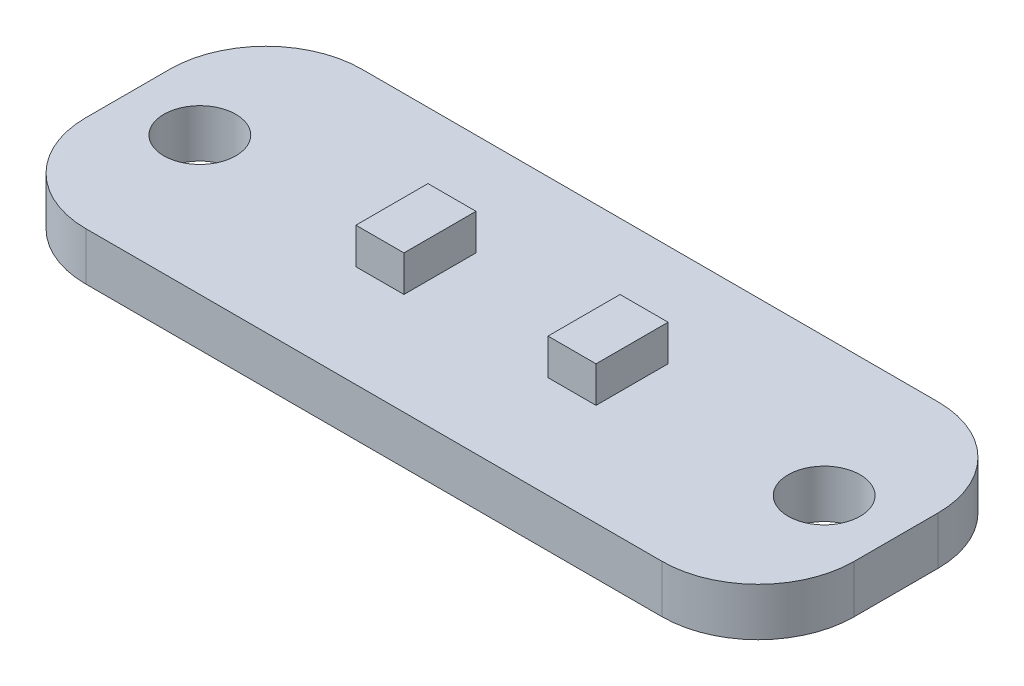
SolidWorks part; units mm, degrees
ref_plane "Front Plane" through (0, 0, 0) normal (0, 0, 1) x (1, 0, 0)
ref_plane "Top Plane" through (0, 0, 0) normal (0, 1, 0) x (1, 0, 0)
ref_plane "Right Plane" through (0, 0, 0) normal (1, 0, 0) x (0, 0, -1)
sketch "Sketch1" plane through (0, 0, 0) normal (0, 1, 0) x (1, 0, 0)
  line L1 (0, 0) -> (32, 0)
  line L2 (0, 0) -> (0, -11.5)
  line L3 (0, -11.5) -> (32, -11.5)
  line L4 (32, 0) -> (32, -11.5)
  dimension "D1" = 32
  dimension "D2" = 11.5
extrude "Boss-Extrude1" add sketch "Sketch1" along normal blind 2
sketch "Sketch2" plane through (0, 2, 0) normal (0, 1, 0) x (1, 0, 0)
  line L0 (32, -11.5) -> (32, 0) construction
  line L1 (0, 0) -> (0, -11.5) construction
  circle A0 centre (3, -5.75) radius 1.5
  circle A1 centre (29, -5.75) radius 1.5
  point P4 (0, 0)
  point P7 (32, -5.75)
  point P10 (0, -5.75)
  dimension "D1" = 3
  dimension "D2" = 3
  dimension "D3" = 3
  dimension "D4" = 3
extrude "Cut-Extrude1" cut sketch "Sketch2" against normal through all
fillet "Fillet1" radius 4 4 edges at (32, 1, 0) (32, 1, 11.5) (0, 1, 0) (0, 1, 11.5)
sketch "Sketch3" plane through (0, 2, 0) normal (0, 1, 0) x (1, 0, 0)
  line L0 (32, -7.5) -> (32, -4) construction
  line L1 (11, -4.25) -> (13, -4.25)
  line L2 (11, -4.25) -> (11, -7.25)
  line L3 (11, -7.25) -> (13, -7.25)
  line L4 (13, -4.25) -> (13, -7.25)
  line L5 (19, -4.25) -> (21, -4.25)
  line L6 (19, -4.25) -> (19, -7.25)
  line L7 (19, -7.25) -> (21, -7.25)
  line L8 (21, -4.25) -> (21, -7.25)
  line L9 (32, -5.75) -> (6.2106, -5.75) construction
  point P12 (13, -5.75)
  point P13 (19, -5.75)
  dimension "D1" = 3
  dimension "D2" = 2
  dimension "D3" = 2
  dimension "D4" = 3
  dimension "D5" = 13
  dimension "D6" = 6
extrude "Boss-Extrude2" add sketch "Sketch3" along normal blind 1.5
